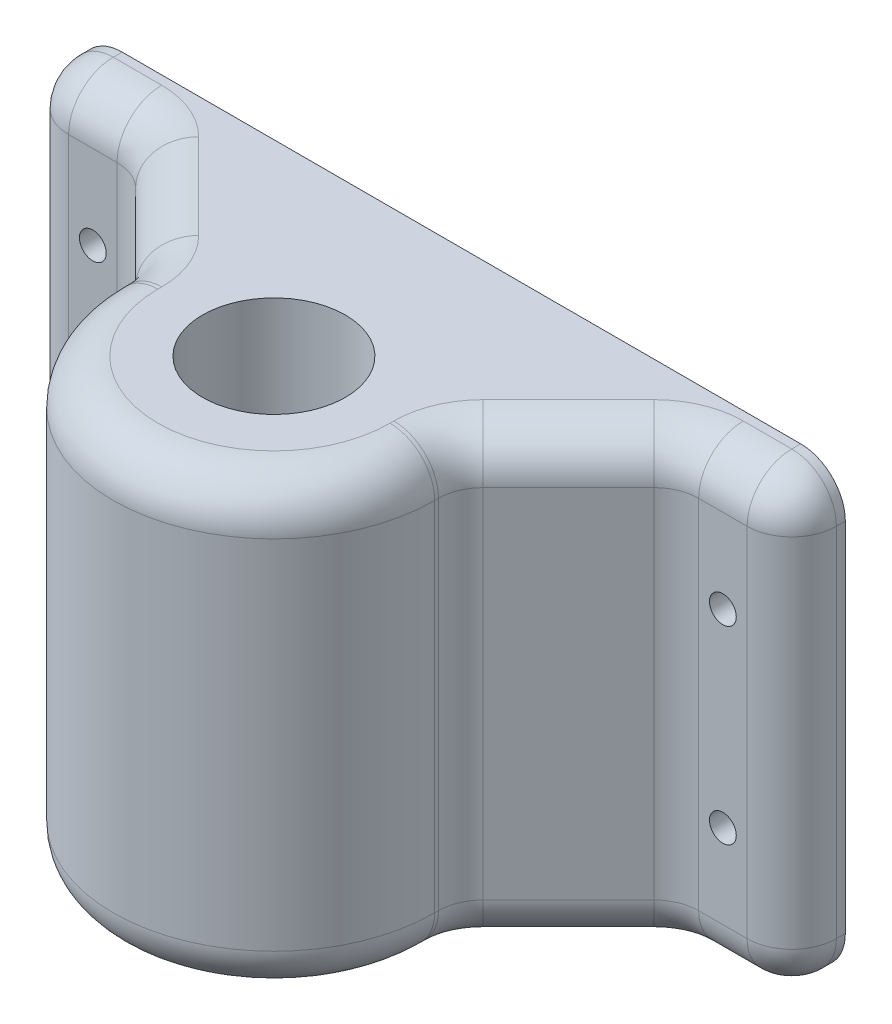
SolidWorks part; units mm, degrees
ref_plane "Front Plane" through (0, 0, 0) normal (0, 0, 1) x (1, 0, 0)
ref_plane "Top Plane" through (0, 0, 0) normal (0, 1, 0) x (1, 0, 0)
ref_plane "Right Plane" through (0, 0, 0) normal (1, 0, 0) x (0, 0, -1)
sketch "Sketch1" plane through (0, 0, 0) normal (0, 0, 1) x (1, 0, 0)
  line L0 (0, 0) -> (86, 0)
  line L1 (86, 0) -> (86, 50)
  line L2 (86, 50) -> (0, 50)
  line L3 (0, 50) -> (0, 0)
  dimension "D1" = 86
  dimension "D2" = 50
extrude "Boss-Extrude2" add sketch "Sketch1" along normal blind 6
sketch "Sketch2" plane through (0, 0, 0) normal (0, -1, 0) x (-1, 0, 0)
  line L0 (-43, -6) -> (-43, -35.2862) construction
  line L1 (0, -6) -> (-86, -6) construction
  line L2 (-61, -21) -> (-61, -6)
  line L3 (-61, -6) -> (-25, -6)
  line L4 (-25, -6) -> (-25, -21)
  arc A2 (-25, -21) -> (-61, -21) centre (-43, -21) cw
extrude "Boss-Extrude3" add sketch "Sketch2" against normal blind 50 contours L4 A2 L2 L3
sketch "Sketch4" plane through (0, 0, 0) normal (0, -1, 0) x (-1, 0, 0)
  line L0 (-25, -6) -> (-61, -6) construction
  line L1 (-43, -6) -> (-43, -21) construction
  circle A0 centre (-43, -21) radius 8
  dimension "D1" = 16
extrude "Cut-Extrude1" cut sketch "Sketch4" against normal blind 121
sketch "Sketch5" plane through (0, 0, 0) normal (0, -1, 0) x (-1, 0, 0)
  line L0 (-61, -6) -> (-73.5, -6)
  line L1 (-61, -6) -> (-86, -6) construction
  line L2 (-73.5, -6) -> (-61, -18.5)
  line L3 (-61, -21) -> (-61, -6) construction
  line L4 (-61, -18.5) -> (-61, -6)
extrude "Boss-Extrude5" add sketch "Sketch5" against normal blind 50
sketch "Sketch6" plane through (0, 0, 0) normal (0, -1, 0) x (-1, 0, 0)
  line L0 (-25, -6) -> (-12.5, -6)
  line L1 (0, -6) -> (-25, -6) construction
  line L2 (-12.5, -6) -> (-25, -18.5)
  line L3 (-25, -6) -> (-25, -21) construction
  line L4 (-25, -18.5) -> (-25, -6)
extrude "Boss-Extrude6" add sketch "Sketch6" against normal blind 50
fillet "Fillet1" radius 5 1 edges at (86, 25, 6)
fillet "Fillet2" radius 5 1 edges at (73.5, 25, 6)
fillet "Fillet3" radius 5 1 edges at (61, 25, 18.5)
fillet "Fillet4" radius 5 3 edges at (12.5, 25, 6) (25, 25, 18.5) (0, 25, 6)
fillet "Fillet5" radius 5 30 edges at (0, 50, 0.5) (1.4645, 50, 4.5355) (7.7145, 50, 6) (12.3423, 50, 6.3806) (18.75, 50, 12.25) (18.75, 0, 12.25) (24.6194, 50, 18.6577) (25, 50, 20.7855) (25, 0, 20.7855) (86, 50, 0.5) (84.5355, 50, 4.5355) (78.2855, 50, 6) (73.6577, 50, 6.3806) (67.25, 50, 12.25) (67.25, 0, 12.25) (61.3806, 50, 18.6577) (61, 0, 20.7855) (61, 50, 20.7855) (0, 0, 0.5) (1.4645, 0, 4.5355) (7.7145, 0, 6) (12.3423, 0, 6.3806) (24.6194, 0, 18.6577) (86, 0, 0.5) (84.5355, 0, 4.5355) (78.2855, 0, 6) (73.6577, 0, 6.3806) (61.3806, 0, 18.6577) (43, 0, 39) (43, 50, 39)
sketch "Sketch7" plane through (0, 0, 6) normal (0, 0, 1) x (1, 0, 0)
  line L0 (7.7145, 45) -> (7.7145, 5) construction
  line L1 (10.4289, 45) -> (5, 45) construction
  line L2 (5, 5) -> (10.4289, 5) construction
  line L3 (7.7145, 25) -> (5, 25) construction
  line L4 (5, 45) -> (5, 5) construction
  line L5 (5, 25) -> (10.4289, 25) construction
  line L6 (10.4289, 5) -> (10.4289, 45) construction
  circle A0 centre (7.7145, 35.6017) radius 1.5
  circle A1 centre (7.7145, 14.3983) radius 1.5
  dimension "D1" = 3
extrude "Cut-Extrude2" cut sketch "Sketch7" against normal blind 50
sketch "Sketch8" plane through (0, 0, 6) normal (0, 0, 1) x (1, 0, 0)
  line L3 (78.2855, 25) -> (81, 25) construction
  line L4 (81, 5) -> (81, 45) construction
  line L5 (81, 25) -> (75.5711, 25) construction
  line L6 (75.5711, 45) -> (75.5711, 5) construction
  line L7 (78.2855, 25) -> (78.2855, 35.6017) construction
  circle A0 centre (78.2855, 35.6017) radius 1.5
  circle A1 centre (78.2855, 14.3983) radius 1.5
  dimension "D2" = 3
  dimension "D1" = 10.6017
extrude "Cut-Extrude4" cut sketch "Sketch8" against normal blind 50
